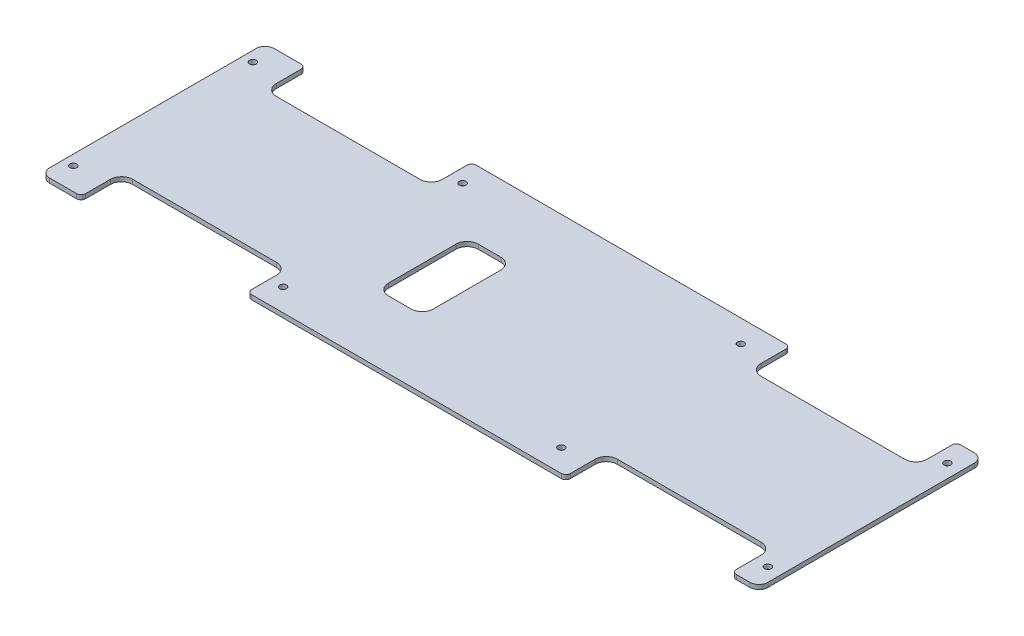
SolidWorks part; units mm, degrees
ref_plane "前视基准面" through (0, 0, 0) normal (0, 0, 1) x (1, 0, 0)
ref_plane "上视基准面" through (0, 0, 0) normal (0, 1, 0) x (1, 0, 0)
ref_plane "右视基准面" through (0, 0, 0) normal (1, 0, 0) x (0, 0, -1)
other "Configuration Table"
sketch "草图1" plane through (0, 0, 0) normal (0, 1, 0) x (1, 0, 0)
  line L0 (4, 50) -> (6, 50)
  line L1 (0, 0) -> (320, 0)
  line L2 (0, -46) -> (0, 46)
  line L4 (320, -46) -> (320, 46)
  line L5 (6, 50) -> (16, 50)
  line L6 (18, 48) -> (18, 37)
  line L7 (23, 32) -> (87, 32)
  line L8 (92, 37) -> (92, 48)
  line L9 (94, 50) -> (232, 50)
  line L10 (234, 48) -> (234, 37)
  line L11 (239, 32) -> (303, 32)
  line L12 (308, 37) -> (308, 48)
  line L13 (310, 50) -> (316, 50)
  line L14 (138.3836, -18.6812) -> (140, -20) construction
  line L15 (138.3836, 18.6812) -> (140, 20) construction
  line L17 (120, 0) -> (120, 15)
  line L18 (125, 20) -> (135, 20)
  line L19 (140, -15) -> (140, 15)
  line L20 (125, -20) -> (135, -20)
  line L21 (120, 0) -> (120, -15)
  line L22 (310, -50) -> (316, -50)
  line L23 (308, -37) -> (308, -48)
  line L24 (239, -32) -> (303, -32)
  line L25 (234, -48) -> (234, -37)
  line L26 (94, -50) -> (232, -50)
  line L27 (92, -37) -> (92, -48)
  line L28 (23, -32) -> (87, -32)
  line L29 (18, -48) -> (18, -37)
  line L30 (6, -50) -> (16, -50)
  line L31 (4, -50) -> (6, -50)
  circle A7 centre (4.5032, 40) radius 1.5
  circle A8 centre (98, 40) radius 1.5
  circle A9 centre (222, 40) radius 1.5
  circle A10 centre (314, 40) radius 1.5
  arc A11 (316, 50) -> (320, 46) centre (316, 46) cw
  arc A12 (0, 46) -> (4, 50) centre (4, 46) cw
  arc A13 (308, 48) -> (310, 50) centre (310, 48) cw
  arc A14 (232, 50) -> (234, 48) centre (232, 48) cw
  arc A15 (92, 48) -> (94, 50) centre (94, 48) cw
  arc A16 (16, 50) -> (18, 48) centre (16, 48) cw
  arc A17 (303, 32) -> (308, 37) centre (303, 37) ccw
  arc A18 (234, 37) -> (239, 32) centre (239, 37) ccw
  arc A19 (87, 32) -> (92, 37) centre (87, 37) ccw
  arc A20 (18, 37) -> (23, 32) centre (23, 37) ccw
  arc A21 (135, 20) -> (140, 15) centre (135, 15) cw
  arc A22 (120, 15) -> (125, 20) centre (125, 15) cw
  arc A23 (120, -15) -> (125, -20) centre (125, -15) ccw
  arc A24 (135, -20) -> (140, -15) centre (135, -15) ccw
  arc A25 (18, -37) -> (23, -32) centre (23, -37) cw
  arc A26 (87, -32) -> (92, -37) centre (87, -37) cw
  arc A27 (234, -37) -> (239, -32) centre (239, -37) cw
  arc A28 (303, -32) -> (308, -37) centre (303, -37) cw
  arc A29 (16, -50) -> (18, -48) centre (16, -48) ccw
  arc A30 (92, -48) -> (94, -50) centre (94, -48) ccw
  arc A31 (232, -50) -> (234, -48) centre (232, -48) ccw
  arc A32 (308, -48) -> (310, -50) centre (310, -48) ccw
  arc A33 (0, -46) -> (4, -50) centre (4, -46) ccw
  arc A34 (316, -50) -> (320, -46) centre (316, -46) ccw
  circle A35 centre (314, -40) radius 1.5
  circle A36 centre (222, -40) radius 1.5
  circle A37 centre (98, -40) radius 1.5
  circle A38 centre (4.5032, -40) radius 1.5
  point P43 (115.4871, 0)
  point P45 (120, 7.5)
  point P100 (140, 0)
  dimension "D1" = 6
  dimension "D2" = 12
  dimension "D3" = 6
  dimension "D4" = 4
  dimension "D5" = 2
  dimension "D6" = 5
  dimension "D10" = 5
  dimension "D7" = 30
  dimension "D8" = 20
  dimension "D9" = 28
extrude "凸台-拉伸1" add sketch "草图1" along normal blind 2 contours L17 A22 L18 A21 L19 L1 L4 A11 L13 A13 L12 A17 L11 A18 L10 A14 L9 A15 L8 A19 L7 A20 L6 A16 L5 L0 A12 L2 A10 A9 A8 A7 | L22 A34 L4 L1 L19 A24 L20 A23 L21 L2 A33 L31 L30 A29 L29 A25 L28 A26 L27 A30 L26 A31 L25 A27 L24 A28 L23 A32 A37 A35 A36 A38
